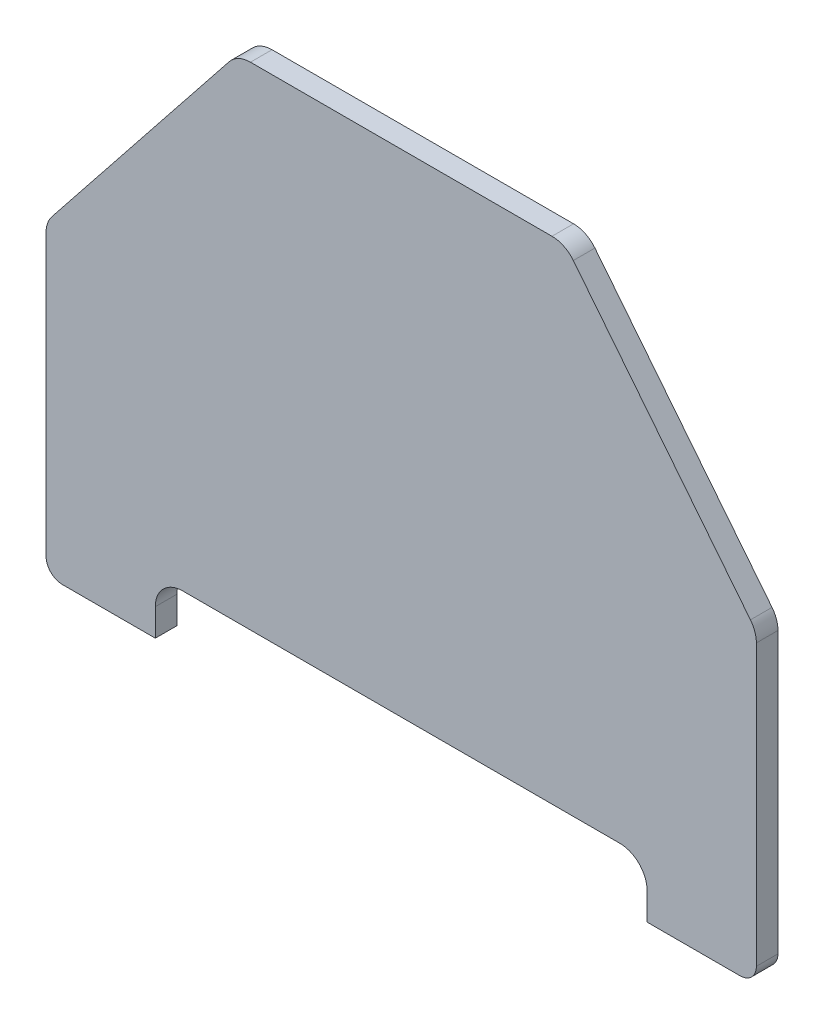
SolidWorks part; units mm, degrees
ref_plane "Front Plane" through (0, 0, 0) normal (0, 0, 1) x (1, 0, 0)
ref_plane "Top Plane" through (0, 0, 0) normal (0, 1, 0) x (1, 0, 0)
ref_plane "Right Plane" through (0, 0, 0) normal (1, 0, 0) x (0, 0, -1)
sketch "Sketch1" plane through (0, 0, 0) normal (0, 0, 1) x (1, 0, 0)
  line L0 (0, 56) -> (35, 100)
  line L2 (0, 56) -> (0, 0)
  line L3 (0, 0) -> (20, 0)
  line L4 (130, 56) -> (130, 0)
  line L8 (20, 0) -> (20, 10)
  line L9 (20, 10) -> (110, 10)
  line L10 (110, 0) -> (110, 10)
  line L11 (35, 100) -> (95, 100)
  line L12 (95, 100) -> (130, 56)
  line L13 (110, 0) -> (130, 0)
  point P0 (0, 0)
  point P2 (0, 0)
  point P4 (29.6881, 64.3447)
  point P12 (0, 38.8109)
  point P15 (33.8536, 71.859)
  point P16 (87.7624, 93.0215)
  dimension "D1" = 130
  dimension "D2" = 20
  dimension "D3" = 56
  dimension "D4" = 60
  dimension "D5" = 10
  dimension "D6" = 100
extrude "Boss-Extrude2" add sketch "Sketch1" along normal blind 3.95
fillet "Fillet1" radius 5 6 edges at (130, 56, 1.975) (95, 100, 1.975) (35, 100, 1.975) (0, 56, 1.975) (110, 10, 1.975) (20, 10, 1.975)
fillet "Fillet2" radius 3 2 edges at (130, 0, 1.975) (0, 0, 1.975)
